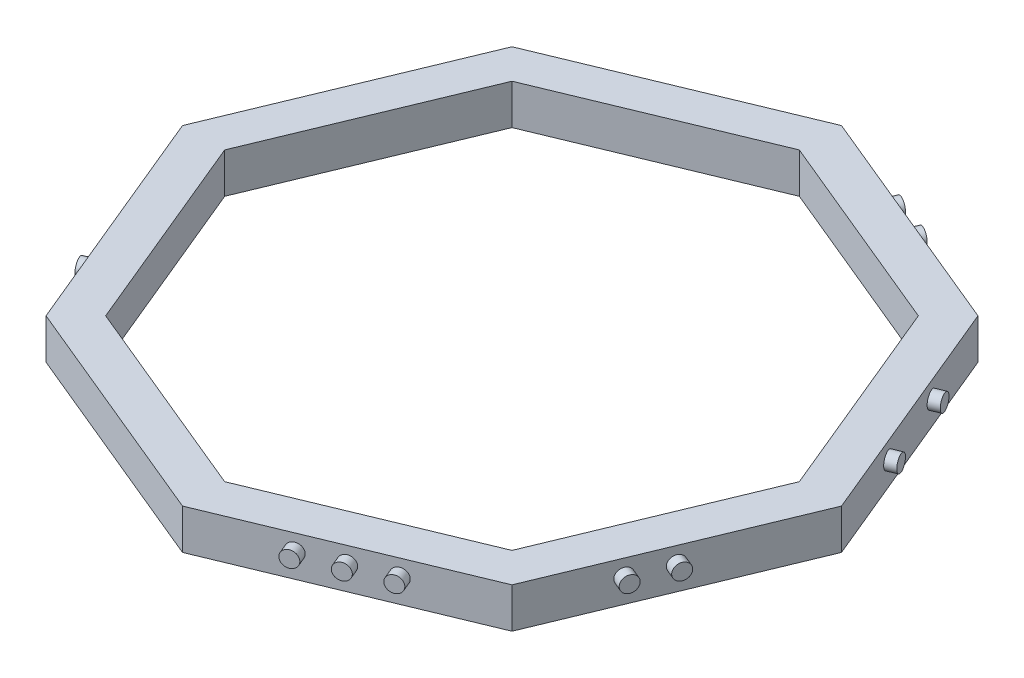
SolidWorks part; units mm, degrees
ref_plane "Front Plane" through (0, 0, 0) normal (0, 0, 1) x (1, 0, 0)
ref_plane "Top Plane" through (0, 0, 0) normal (0, 1, 0) x (1, 0, 0)
ref_plane "Right Plane" through (0, 0, 0) normal (1, 0, 0) x (0, 0, -1)
sketch "Sketch3" plane through (0, 0, 0) normal (0, 1, 0) x (1, 0, 0)
  line L1 (41, 0) -> (28.9914, 28.9914)
  line L2 (28.9914, 28.9914) -> (0, 41)
  line L3 (0, 41) -> (-28.9914, 28.9914)
  line L4 (-28.9914, 28.9914) -> (-41, 0)
  line L5 (-41, 0) -> (-28.9914, -28.9914)
  line L6 (-28.9914, -28.9914) -> (0, -41)
  line L7 (0, -41) -> (28.9914, -28.9914)
  line L8 (28.9914, -28.9914) -> (41, 0)
  circle A0 centre (0, 0) radius 37.8791 construction
  dimension "D1" = 41
extrude "Boss-Extrude1" add sketch "Sketch3" along normal blind 5
sketch "Sketch5" plane through (0, 5, 0) normal (0, 1, 0) x (1, 0, 0)
  line L1 (35.75, 0) -> (25.2791, 25.2791)
  line L2 (25.2791, 25.2791) -> (0, 35.75)
  line L3 (0, 35.75) -> (-25.2791, 25.2791)
  line L4 (-25.2791, 25.2791) -> (-35.75, 0)
  line L5 (-35.75, 0) -> (-25.2791, -25.2791)
  line L6 (-25.2791, -25.2791) -> (0, -35.75)
  line L7 (0, -35.75) -> (25.2791, -25.2791)
  line L8 (25.2791, -25.2791) -> (35.75, 0)
  circle A0 centre (0, 0) radius 33.0287 construction
  dimension "D1" = 35.75
extrude "Cut-Extrude1" cut sketch "Sketch5" against normal blind 5
sketch "Sketch6" plane through (14.4957, 0, 34.9957) normal (0.3827, 0, 0.9239) x (0.9239, 0, -0.3827)
  circle A0 centre (0, 3) radius 1
  circle A1 centre (-5, 3) radius 1
  circle A2 centre (5, 3) radius 1
sketch "Sketch7" plane through (-34.9957, 0, 14.4957) normal (-0.9239, 0, 0.3827) x (0.3827, 0, 0.9239)
  circle A0 centre (5, 3) radius 1
sketch "Sketch8" plane through (-34.9957, 0, -14.4957) normal (-0.9239, 0, -0.3827) x (-0.3827, 0, 0.9239)
  circle A0 centre (0, 3) radius 1
sketch "Sketch9" plane through (-14.4957, 0, -34.9957) normal (-0.3827, 0, -0.9239) x (-0.9239, 0, 0.3827)
  circle A0 centre (-5, 3) radius 1
sketch "Sketch10" plane through (14.4957, 0, -34.9957) normal (0.3827, 0, -0.9239) x (-0.9239, 0, -0.3827)
  circle A0 centre (0, 3) radius 1
  circle A1 centre (5, 3) radius 1
sketch "Sketch11" plane through (34.9957, 0, -14.4957) normal (0.9239, 0, -0.3827) x (-0.3827, 0, -0.9239)
  circle A0 centre (5, 3) radius 1
  circle A1 centre (-5, 3) radius 1
sketch "Sketch12" plane through (34.9957, 0, 14.4957) normal (0.9239, 0, 0.3827) x (0.3827, 0, -0.9239)
  circle A0 centre (0, 3) radius 1
  circle A1 centre (-5, 3) radius 1
extrude "Boss-Extrude5" add sketch "Sketch6" along normal blind 1.25 contours A2 | A1 | A0
extrude "Boss-Extrude6" add sketch "Sketch7" along normal blind 1.25 contours A0
extrude "Boss-Extrude7" add sketch "Sketch8" along normal blind 1.25 contours A0
extrude "Boss-Extrude8" add sketch "Sketch9" along normal blind 1.25 contours A0
extrude "Boss-Extrude12" add sketch "Sketch10" along normal blind 1.25 contours A0 | A1
extrude "Boss-Extrude13" add sketch "Sketch11" along normal blind 1.25 contours A1 | A0
extrude "Boss-Extrude14" add sketch "Sketch12" along normal blind 1.25 contours A1 | A0
